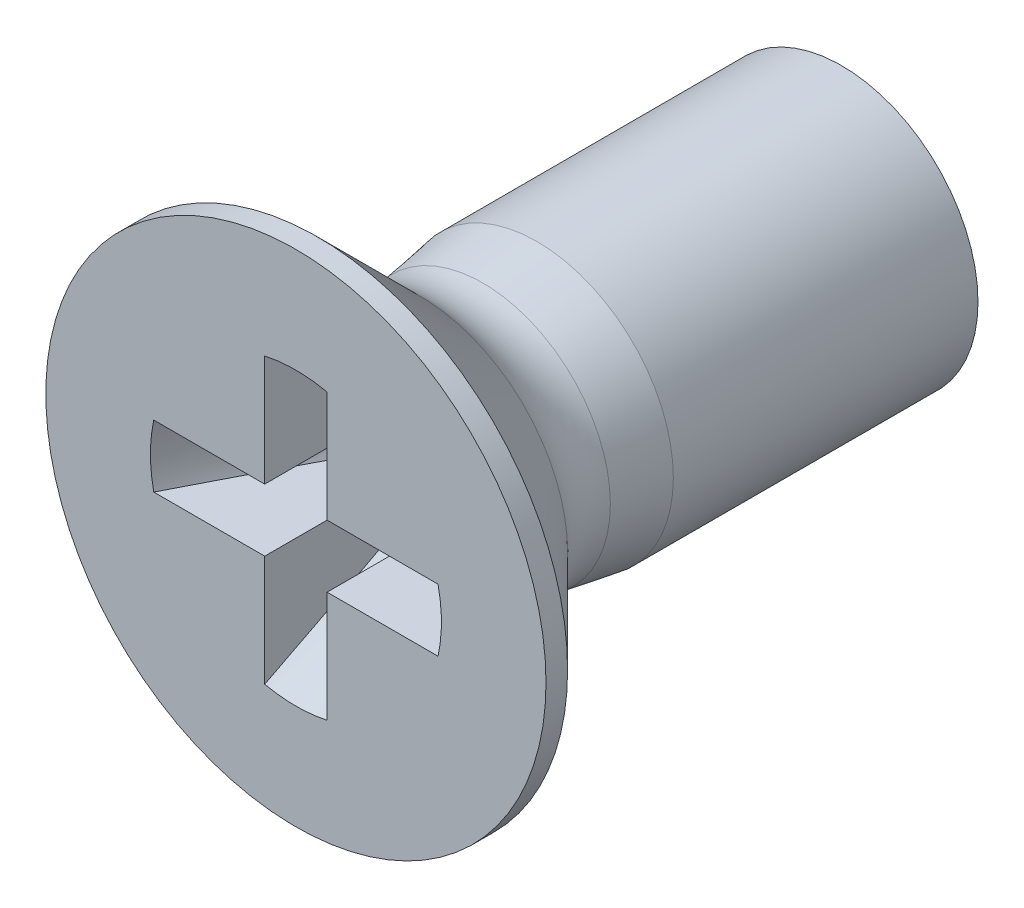
SolidWorks part; units mm, degrees
material "Alloy Steel"
ref_plane "Спереди" through (0, 0, 0) normal (0, 0, 1) x (1, 0, 0)
ref_plane "Сверху" through (0, 0, 0) normal (0, 1, 0) x (1, 0, 0)
ref_plane "Справа" through (0, 0, 0) normal (1, 0, 0) x (0, 0, -1)
sketch "Sketch1" plane through (0, 0, 0) normal (1, 0, 0) x (0, 0, -1)
  line L0 (0, 0) -> (6, 0) construction
  line L1 (0, 0) -> (0, 2.75)
  line L2 (0, 2.75) -> (0.2375, 2.75)
  line L7 (6, 1.65) -> (6, 0)
  line L10 (6, 1.65) -> (6, 0) construction
  line L11 (0.2375, 2.75) -> (1.65, 1.3375)
  line L15 (1.65, 1.65) -> (6, 1.65)
  line L20 (0, 0) -> (6, 0)
  line L21 (1.65, 1.3375) -> (1.65, 1.65)
  line L22 (0, 0) -> (-0.8225, 0) construction
  line L23 (1.65, 1.65) -> (1.65, 4.65) construction
  dimension "D1" = 45
  dimension "Dk" = 5.5
  dimension "L" = 6
  dimension "k" = 1.65
  dimension "d2" = 2.675
  dimension "d" = 3
  dimension "D3" = 3.3
revolve "RevolveBase" add sketch "Sketch1" angle 360 about L0
sketch "Sketch3" plane through (0, 0, 0) normal (0, 0, 1) x (1, 0, 0)
  line L0 (0, 2.75) -> (0, 0) construction
  line L1 (0, 0) -> (2.75, 0) construction
  line L2 (-0.3429, 0) -> (0.3429, 0)
  line L3 (0.3429, 0) -> (0.3429, 1.5628)
  line L4 (-0.3429, 0) -> (-0.3429, 1.5628)
  line L5 (0.3429, 0) -> (-0.3429, 0.6859) construction
  circle A0 centre (0, 0) radius 2.75 construction
  arc A1 (0.3429, 1.5628) -> (-0.3429, 1.5628) centre (0, 0) ccw
  point P5 (0, 1.6)
  dimension "m" = 3.2
  dimension "D1" = 45
  dimension "b" = 0.97
extrude "Cross" cut sketch "Sketch3" against normal blind 3.2
pattern_circular "CirPattern1" count 4 over 360 about axis through (0, 0, 0) along (0, 0, 1) of "Cross"
sketch "Sketch4" plane through (0, 0, 0) normal (0, 0, 1) x (1, 0, 0)
  line L0 (0, 2.75) -> (0, -2.75) construction
  line L1 (-2.75, 0) -> (2.75, 0) construction
  line L2 (0, 0) -> (-1.9445, 1.9445) construction
  line L3 (-1.1314, 1.1314) -> (-0.3392, 0)
  line L4 (-0.3392, 0) -> (0, 0)
  line L5 (0, 0) -> (0, 0.3392)
  line L6 (0, 0.3392) -> (-1.1314, 1.1314)
  circle A0 centre (0, 0) radius 2.75 construction
  dimension "D1" = 45
  dimension "D2" = 10
  dimension "D3" = 10
  dimension "D4" = 1.6
extrude "Cross2" [suppressed] cut sketch "Sketch4" against normal blind 2.56
pattern_circular "CirPattern2" [suppressed] count 4 over 360
sketch "Sketch5" plane through (0, 0, 0) normal (1, 0, 0) x (0, 0, -1)
  line L0 (0, 0) -> (6, 0) construction
  line L1 (0, 2.75) -> (0, -2.75) construction
  line L2 (6, -1.65) -> (6, 1.65) construction
  line L8 (0, 2.102) -> (0, 1.6)
  line L9 (0, 1.6) -> (1.9355, 0.635)
  line L10 (1.9355, 0.635) -> (2.2731, 0)
  line L11 (0, 2.102) -> (0.8855, 2.102)
  line L13 (1.65, 1.3375) -> (1.65, 1.5)
  line L14 (0.8855, 2.102) -> (1.65, 1.3375)
  line L17 (1.65, 1.5) -> (6, 1.5)
  line L18 (6, 1.5) -> (6, 0)
  line L19 (6, 0) -> (2.2731, 0)
  dimension "D2" = 3.2
  dimension "g" = 1.27
  dimension "D4" = 0.502
  dimension "D8" = 6
  dimension "D9" = 3
  dimension "D10" = 26.5
  dimension "D3" = 28
  dimension "D6" = 1.65
  dimension "D5" = 2.675
  dimension "D7" = 45
revolve "RevolveRod" add sketch "Sketch5" angle 360 about L0
sketch "Sketch6" plane through (0, 0, 0) normal (1, 0, 0) x (0, 0, -1)
  line L0 (0, 0) -> (1.65, 0) construction
  line L1 (1.65, 0) -> (1.65, 1.3375) construction
  line L2 (1.65, 1.3375) -> (0.3125, 2.675)
  dimension "D1" = 1.65
  dimension "D2" = 2.675
  dimension "D3" = 45
  dimension "D4" = 5.35
surface "Surface" sketch "Sketch6" parameters "D1"=360
sketch "Sketch7" plane through (0, 0, 0) normal (1, 0, 0) x (0, 0, -1)
  line L0 (0, 0) -> (3.5808, 0) construction
  line L1 (0, 0) -> (0, 2.1492) construction
  line L2 (1.65, 3.5) -> (1.65, 1.3375)
  line L3 (1.65, 1.3375) -> (2.65, 1.5)
  line L5 (6, 3.5) -> (1.65, 3.5)
  line L6 (2.65, 1.5) -> (6, 1.5)
  line L7 (6, 1.5) -> (6, 3.5)
  dimension "D1" = 1.65
  dimension "D2" = 2.675
  dimension "D3" = 3
  dimension "D5" = 1
  dimension "D4" = 2
  dimension "D6" = 6
revolve "CutBody" cut sketch "Sketch7" angle 360 about L0
cosmetic thread "Cosmetic Thread1" parameters "D1"=4.35, "D2"=2.459
fillet "Fillet1" radius 0.8 1 edges at (1.3375, 0, -1.65)
sketch "Sketch8" [suppressed] plane through (0, 0, 0) normal (1, 0, 0) x (0, 0, -1)
  line L0 (0, 0) -> (3.4085, 0) construction
  line L1 (0, 7.9) -> (0, -7.9) construction
  line L2 (0, 0) -> (0, 1.7584) construction
  line L3 (4.65, 4.594) -> (4.65, 3.594)
  line L4 (4.65, 3.594) -> (13.8, 3.594)
  line L5 (13.8, 3.594) -> (13.8, 4.594)
  line L6 (13.8, 4.594) -> (4.65, 4.594)
  dimension "D1" = 1.65
  dimension "D2" = 2.675
  dimension "D3" = 1.65
  dimension "D4" = 1
revolve "CutBody2" [suppressed] cut sketch "Sketch8" angle 360 about L0
fillet "Fillet2" [suppressed] radius 0.8
equation "\"D1@Cross\"= \"m@Sketch3\""
equation "\"D4@Sketch4\"=\"m@Sketch3\"/2"
equation "\"D1@Cross2\"=\"m@Sketch3\"*0.8"
equation "\"D2@Sketch5\"=\"m@Sketch3\""
equation "\"D8@Sketch5\"=\"L@Sketch1\""
equation "\"D9@Sketch5\"=\"d@Sketch1\""
equation "\"1б3\"=1.19"
equation "\"D6@Sketch5\"= \"k@Sketch1\""
equation "\"D1@Sketch6\"= \"k@Sketch1\""
equation "\"D2@Sketch6\"= \"d2@Sketch1\""
equation "\"D4@Sketch6\"= 2 * \"d2@Sketch1\""
equation "\"D5@Sketch5\"=\"d2@Sketch1\""
equation "\"D2@Sketch7\"=\"d2@Sketch1\""
equation "\"D3@Sketch7\"=\"d@Sketch1\""
equation "\"D2@Sketch8\"=\"d2@Sketch1\""
equation "\"D1@Sketch8\"=\"k@Sketch1\""
equation "\"D3@Sketch8\"=\"D1@Sketch7\""
equation "\"D1@Fillet2\"=\"D1@Fillet1\""
equation "\"D3@Sketch1\"=\"d@Sketch1\"+0.3"
equation "\"D6@Sketch7\"=\"L@Sketch1\""
